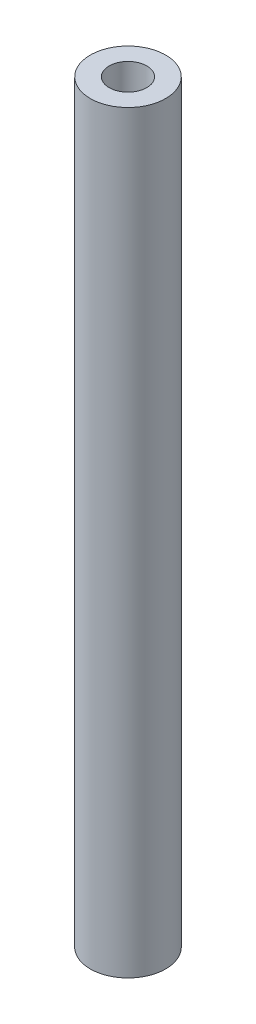
SolidWorks part; units mm, degrees
ref_plane "Front Plane" through (0, 0, 0) normal (0, 0, 1) x (1, 0, 0)
ref_plane "Top Plane" through (0, 0, 0) normal (0, 1, 0) x (1, 0, 0)
ref_plane "Right Plane" through (0, 0, 0) normal (1, 0, 0) x (0, 0, -1)
sketch "Sketch1" plane through (0, 0, 0) normal (0, 1, 0) x (1, 0, 0)
  circle A0 centre (0, 0) radius 1.5
  circle A1 centre (0, 0) radius 3
  dimension "D1" = 3
  dimension "D2" = 1.5
extrude "Boss-Extrude1" add sketch "Sketch1" along normal blind 60
